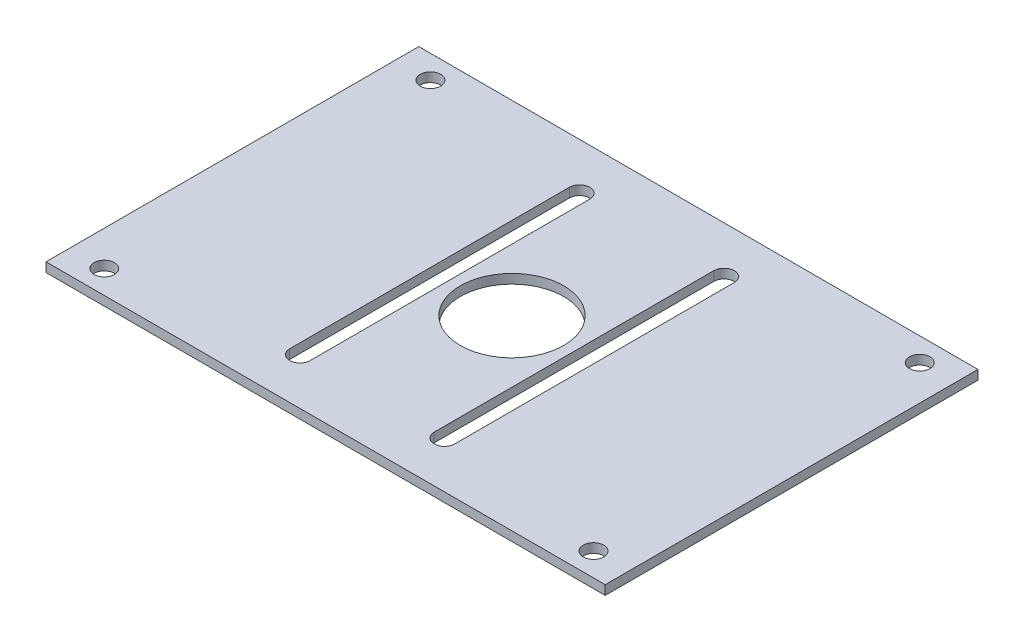
SolidWorks part; units mm, degrees
ref_plane "Front Plane" through (0, 0, 0) normal (0, 0, 1) x (1, 0, 0)
ref_plane "Top Plane" through (0, 0, 0) normal (0, 1, 0) x (1, 0, 0)
ref_plane "Right Plane" through (0, 0, 0) normal (1, 0, 0) x (0, 0, -1)
sketch "Sketch1" plane through (0, 0, 0) normal (0, 1, 0) x (1, 0, 0)
  line L0 (0, 0) -> (0, -34.1005) construction
  line L1 (-60, 40) -> (60, 40)
  line L2 (-60, 40) -> (-60, -40)
  line L3 (-60, -40) -> (60, -40)
  line L4 (60, 40) -> (60, -40)
  line L5 (-60, 40) -> (60, -40) construction
  line L6 (-60, -40) -> (60, 40) construction
  line L7 (0, 0) -> (57.0334, 0) construction
  line L8 (-17.7, -30) -> (-17.7, 30)
  line L9 (-13.3, 30) -> (-13.3, -30)
  line L10 (-17.7, 0) -> (-13.3, 0) construction
  line L11 (-15.5, -30) -> (-15.5, 30) construction
  line L12 (13.3, 30) -> (13.3, -30)
  line L13 (17.7, -30) -> (17.7, 30)
  circle A0 centre (-52.5, 35) radius 2.2
  circle A1 centre (52.5, 35) radius 2.2
  circle A2 centre (52.5, -35) radius 2.2
  circle A3 centre (-52.5, -35) radius 2.2
  circle A4 centre (0, 0) radius 11.1
  arc A5 (-13.3, 30) -> (-17.7, 30) centre (-15.5, 30) ccw
  arc A6 (-13.3, -30) -> (-17.7, -30) centre (-15.5, -30) cw
  arc A7 (13.3, 30) -> (17.7, 30) centre (15.5, 30) cw
  arc A8 (13.3, -30) -> (17.7, -30) centre (15.5, -30) ccw
  point P0 (0, 0)
  dimension "D3" = 4.4
  dimension "D4" = 5
  dimension "D5" = 22.2
  dimension "D7" = 2.2
  dimension "D8" = 10
  dimension "D1" = 80
  dimension "D2" = 120
  dimension "D6" = 60
  dimension "D9" = 15.5
extrude "Boss-Extrude1" add sketch "Sketch1" along normal blind 2
